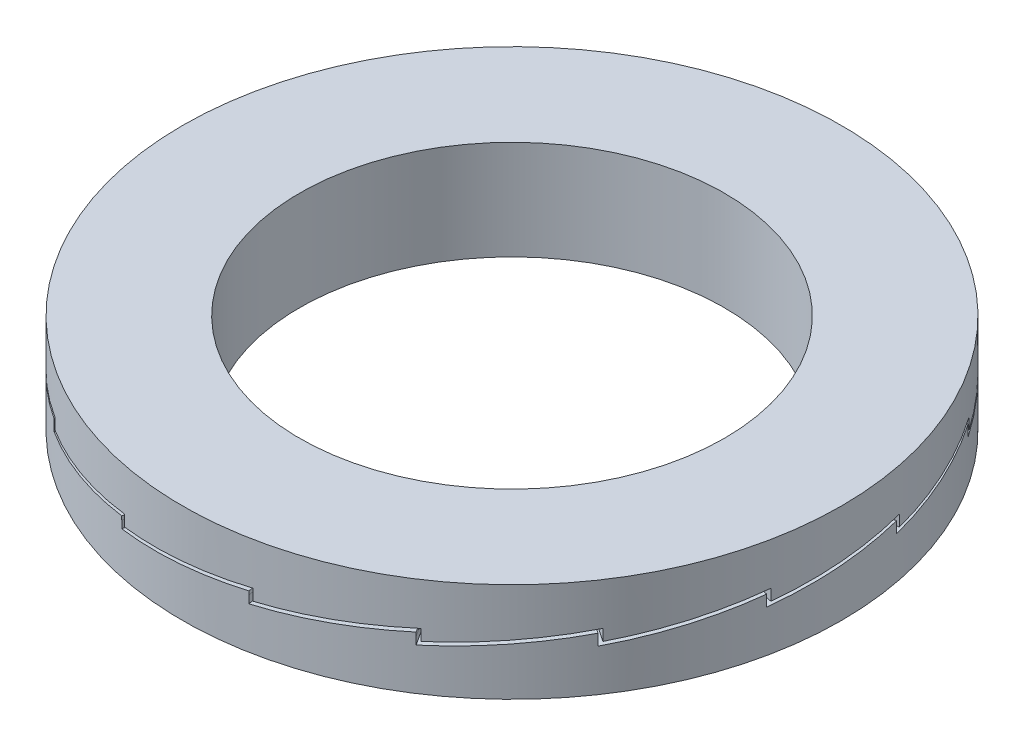
SolidWorks part; units mm, degrees
material "PW100:Mi:0:30:Re:13:"
ref_plane "Front" through (0, 0, 0) normal (0, 0, 1) x (1, 0, 0)
ref_plane "Top" through (0, 0, 0) normal (0, 1, 0) x (1, 0, 0)
ref_plane "Right" through (0, 0, 0) normal (1, 0, 0) x (0, 0, -1)
sketch "Support-Top-Body" plane through (0, 0, 0) normal (0, 1, 0) x (1, 0, 0)
  line L0 (0, 0) -> (5.35, 0) construction
  line L1 (5.35, 0) -> (8.3, 0) construction
  circle A0 centre (0, 0) radius 8.3
  circle A1 centre (0, 0) radius 5.35
  dimension "Diam-Inner" = 10.7
  dimension "Diam-Outer" = 16.6
sketch "Support-Front-Body" plane through (0, 0, 0) normal (0, 0, 1) x (1, 0, 0)
  line L0 (5.35, 1.15) -> (5.45, 1.25)
  line L1 (5.35, 1.25) -> (8.3, 1.25)
  line L2 (5.35, 1.25) -> (5.35, -1.25)
  line L3 (5.35, -1.25) -> (8.3, -1.25)
  line L4 (8.3, 1.25) -> (8.3, -1.25)
  line L5 (0, -1.25) -> (0, 1.25) construction
  line L6 (5.35, 1.25) -> (0, 1.25) construction
  line L7 (5.35, -1.25) -> (0, -1.25) construction
  line L8 (5.35, -1.15) -> (5.45, -1.25)
  line L9 (8.3, 0) -> (0, 0) construction
  dimension "Thickness" = 2.5
  dimension "Angel-Cut" = 45
  dimension "Dist-Cut" = 0.1
sketch "Sketch3" plane through (0, 0, 0) normal (0, 0, 1) x (1, 0, 0)
  line L0 (0, -1.25) -> (0, 1.25) construction
  line L1 (0, -1.25) -> (0, 1.25) construction
  line L4 (8.3, 1.25) -> (5.35, 1.25)
  line L5 (8.3, -1.25) -> (8.3, 1.25)
  line L6 (5.35, -1.25) -> (8.3, -1.25)
  line L7 (5.35, 1.25) -> (5.35, -1.25)
  line L8 (8.3, 1.25) -> (5.35, 1.25)
  line L9 (8.3, -1.25) -> (8.3, 1.25)
  line L10 (5.35, -1.25) -> (8.3, -1.25)
  line L11 (5.35, 1.25) -> (5.35, -1.25)
  dimension "D1" = 0
revolve "Base-Revolve" add sketch "Sketch3" angle 360 about L1
sketch "Support-Top-Cut" plane through (0, 0, 0) normal (0, 1, 0) x (1, 0, 0)
  line L0 (7.6323, 0) -> (8.3, 0)
  line L1 (7.6323, 0) -> (7.6323, 7.6323) construction
  line L3 (7.6323, 7.6323) -> (0, 7.6323) construction
  line L5 (7.6323, 7.6323) -> (8.3, 0) construction
  line L6 (0, 0) -> (0, 7.6323) construction
  line L7 (0, 0) -> (7.6323, 0) construction
  line L8 (0, 0) -> (7.4856, 1.489) construction
  line L9 (0, 0) -> (7.4856, -1.489) construction
  line L10 (7.4856, 1.489) -> (8.3, 1.651)
  line L11 (7.4856, -1.489) -> (8.3, -1.651)
  line L12 (7.6323, -1.5182) -> (7.6323, 1.5182) construction
  line L13 (8.3, -1.651) -> (8.3, 1.651) construction
  circle A0 centre (0, 0) radius 7.6323 construction
  dimension "Angle-Cut-Length" = 5
ref_plane "Plane-Cut-Start" through (7.6323, 0, 0) normal (1, 0, 0) x (0, 0, -1)
ref_plane "Plane-Cut-End" through (8.3, 0, 0) normal (1, 0, 0) x (0, 0, -1)
sketch "Support-Plane-Cut-Start" plane through (7.6323, 0, 0) normal (1, 0, 0) x (0, 0, -1)
  line L0 (-1.6017, 0) -> (-1.5182, 0)
  line L1 (-1.5182, 0) -> (-1.5182, -0.0909)
  line L2 (-1.5182, -0.0909) -> (1.5182, 0.1748)
  line L3 (1.5182, 0.1748) -> (1.5182, 0)
  line L4 (1.5182, 0) -> (1.4346, 0)
  line L5 (1.4346, 0) -> (1.4346, 0.0836)
  line L6 (1.4346, 0.0836) -> (-1.6017, -0.1821)
  line L7 (-1.6017, -0.1821) -> (-1.6017, 0)
  line L8 (5.35, 0) -> (-5.35, 0) construction
  line L13 (1.4346, 0.0836) -> (1.4273, 0.1668) construction
  line L14 (0, -0.0419) -> (0, 0.0419) construction
  dimension "Angle-Cut" = 5
sketch "Sketch12" plane through (7.6323, 0, 0) normal (1, 0, 0) x (0, 0, -1)
  line L8 (-1.6017, -0.1821) -> (1.4346, 0.0836)
  line L9 (1.4346, 0.0836) -> (1.4346, 0)
  line L10 (1.4346, 0) -> (1.5182, 0)
  line L11 (1.5182, 0) -> (1.5182, 0.1748)
  line L12 (1.5182, 0.1748) -> (-1.5182, -0.0909)
  line L13 (-1.5182, -0.0909) -> (-1.5182, 0)
  line L14 (-1.5182, 0) -> (-1.6017, 0)
  line L15 (-1.6017, 0) -> (-1.6017, -0.1821)
  line L16 (-1.6017, -0.1821) -> (1.4346, 0.0836)
  line L17 (1.4346, 0.0836) -> (1.4346, 0)
  line L18 (1.4346, 0) -> (1.5182, 0)
  line L19 (1.5182, 0) -> (1.5182, 0.1748)
  line L20 (1.5182, 0.1748) -> (-1.5182, -0.0909)
  line L21 (-1.5182, -0.0909) -> (-1.5182, 0)
  line L22 (-1.5182, 0) -> (-1.6017, 0)
  line L23 (-1.6017, 0) -> (-1.6017, -0.1821)
  dimension "D1" = 0
sketch "Sketch15" plane through (8.3, 0, 0) normal (1, 0, 0) x (0, 0, -1)
  line L0 (-1.7452, 0) -> (-1.651, 0)
  line L1 (-1.651, 0) -> (-1.651, -0.1025)
  line L2 (-1.651, -0.1025) -> (1.651, 0.1864)
  line L3 (1.651, 0.1864) -> (1.651, 0)
  line L4 (1.651, 0) -> (1.5567, 0)
  line L5 (1.5567, 0) -> (1.5567, 0.0943)
  line L6 (1.5567, 0.0943) -> (-1.7452, -0.1946)
  line L7 (-1.7452, -0.1946) -> (-1.7452, 0)
  line L8 (-1.651, 0) -> (1.651, 0) construction
  line L9 (-1.6017, -0.1821) -> (1.4346, 0.0836) construction
  line L10 (7.6323, 0) -> (-7.6323, 0) construction
  line L11 (1.5182, 0.1748) -> (-1.5182, -0.0909) construction
loft "Cut-Profile" cut profiles "Sketch12", "Sketch15"
pattern_circular "Pattern-Cut-Profile" count 16 every 22.5 about axis through (0, -1.25, 0) along (0, 1, 0) of "Cut-Profile"
sketch "Sketch17" plane through (0, 0, 0) normal (0, 0, 1) x (1, 0, 0)
  line L0 (5.35, 1.25) -> (5.35, -1.25) construction
  line L1 (5.35, 1.25) -> (8.3, 1.25) construction
  line L2 (5.35, 1.15) -> (5.45, 1.25) construction
  line L4 (5.35, 1.25) -> (5.45, 1.25)
  line L5 (5.35, 1.15) -> (5.45, 1.25)
  line L6 (0, 0) -> (0, 1.25) construction
  line L7 (0, -1.25) -> (0, 1.25) construction
  line L8 (5.35, -1.15) -> (5.45, -1.25) construction
  line L9 (5.35, -1.25) -> (8.3, -1.25) construction
  line L10 (5.35, -1.15) -> (5.45, -1.25)
  line L11 (5.35, -1.25) -> (5.45, -1.25)
  line L12 (5.35, 1.25) -> (5.35, 1.15)
  line L13 (5.35, -1.15) -> (5.35, -1.25)
revolve "Cosmetic-Cut" [suppressed] cut sketch "Sketch17" angle 360 about L6
equation "\"Num-Cut-Profile@Pattern-Cut-Profile\" =360 / \"Angle-Cut-Width@Pattern-Cut-Profile\""
